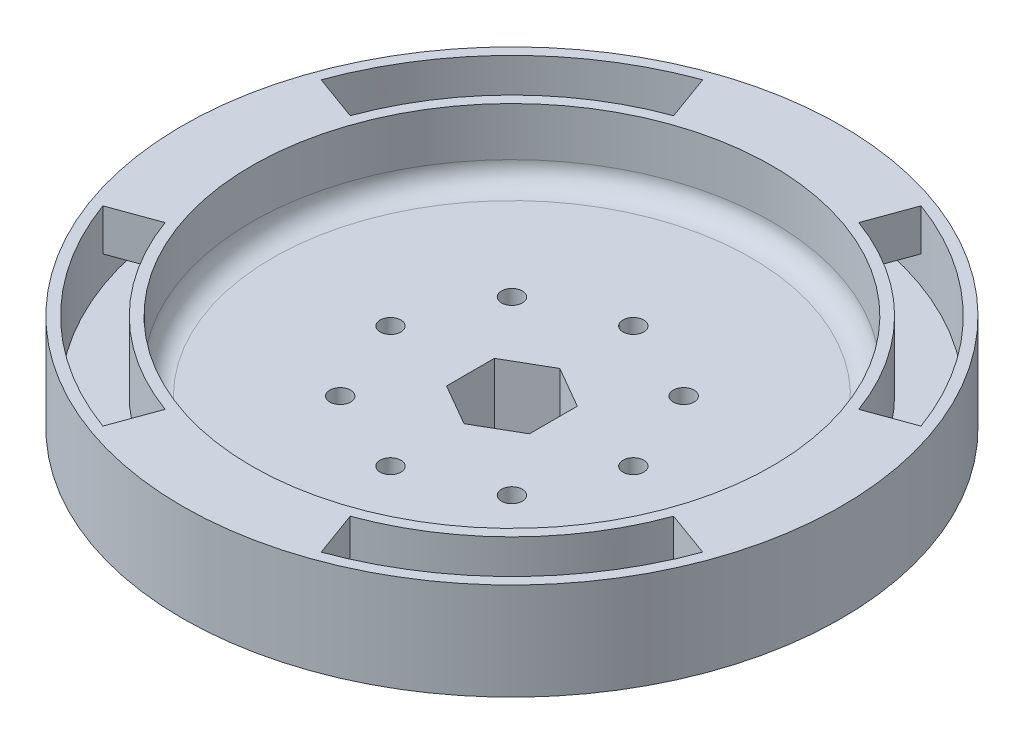
SolidWorks part; units mm, degrees
material "聚脂树脂"
ref_plane "前视基准面" through (0, 0, 0) normal (0, 0, 1) x (1, 0, 0)
ref_plane "上视基准面" through (0, 0, 0) normal (0, 1, 0) x (1, 0, 0)
ref_plane "右视基准面" through (0, 0, 0) normal (1, 0, 0) x (0, 0, -1)
other "Configuration Table"
sketch "草图1" plane through (0, 0, 0) normal (0, 1, 0) x (1, 0, 0)
  line L0 (0, 0) -> (29.5032, 0) construction
  line L1 (0, 0) -> (0, 22.1158) construction
  line L2 (0, 0) -> (19.7523, 19.7523) construction
  line L4 (0, 6.8993) -> (-5.975, 3.4497)
  line L5 (-5.975, 3.4497) -> (-5.975, -3.4497)
  line L6 (-5.975, -3.4497) -> (0, -6.8993)
  line L7 (0, -6.8993) -> (5.975, -3.4497)
  line L8 (5.975, -3.4497) -> (5.975, 3.4497)
  line L9 (5.975, 3.4497) -> (0, 6.8993)
  circle A0 centre (0, 0) radius 21.5
  circle A1 centre (12.3744, 12.3744) radius 1.5
  circle A3 centre (12.3744, -12.3744) radius 1.5
  circle A4 centre (-12.3744, -12.3744) radius 1.5
  circle A5 centre (-12.3744, 12.3744) radius 1.5
  circle A7 centre (0, 17.5) radius 1.5
  circle A8 centre (17.5, 0) radius 1.5
  circle A9 centre (0, -17.5) radius 1.5
  circle A10 centre (-17.5, 0) radius 1.5
  circle A11 centre (0, 0) radius 5.975 construction
  point P7 (0, 6.8993)
  point P25 (0, 0)
  dimension "D1" = 43
  dimension "D2" = 11.95
  dimension "D3" = 3
  dimension "D6" = 2
  dimension "D4" = 17.5
  dimension "D5" = 45
extrude "凸台-拉伸1" add sketch "草图1" along normal blind 4
sketch "草图9" plane through (0, 0, 0) normal (0, -1, 0) x (1, 0, 0)
  line L0 (-5.975, -3.4497) -> (-5.975, 3.4497) construction
  line L1 (0, -6.8993) -> (-5.975, -3.4497) construction
  line L2 (5.975, -3.4497) -> (0, -6.8993) construction
  line L3 (5.975, 3.4497) -> (5.975, -3.4497) construction
  line L4 (0, 6.8993) -> (5.975, 3.4497) construction
  line L5 (-5.975, 3.4497) -> (0, 6.8993) construction
  line L6 (-5.975, -3.4497) -> (-5.975, 3.4497)
  line L7 (0, -6.8993) -> (-5.975, -3.4497)
  line L8 (5.975, -3.4497) -> (0, -6.8993)
  line L9 (5.975, 3.4497) -> (5.975, -3.4497)
  line L10 (0, 6.8993) -> (5.975, 3.4497)
  line L11 (-5.975, 3.4497) -> (0, 6.8993)
  circle A0 centre (0, 0) radius 9.75
  dimension "D1" = 19.5
extrude "凸台-拉伸4" add sketch "草图9" along normal blind 5
sketch "草图10" plane through (0, -5, 0) normal (0, -1, 0) x (1, 0, 0)
  circle A0 centre (0, 0) radius 9.75
  circle A1 centre (0, 0) radius 2
  dimension "D1" = 4
  dimension "D2" = 19.5
extrude "凸台-拉伸5" add sketch "草图10" along normal blind 5
sketch "草图11" plane through (0, -10, 0) normal (0, -1, 0) x (1, 0, 0)
  line L0 (0, 0) -> (0, 28.5719) construction
  line L1 (0, 0) -> (35.6203, -20.5654) construction
  line L2 (0, 0) -> (-22.187, -12.8097) construction
  line L3 (2, 0) -> (8.8992, -3.9833)
  line L4 (1, -1.7321) -> (7.8992, -5.7153)
  line L5 (-1, -1.7321) -> (-7.8992, -5.7153)
  line L6 (-2, 0) -> (-8.8992, -3.9833)
  line L7 (1, 1.7321) -> (1, 9.6986)
  line L8 (-1, 1.7321) -> (-1, 9.6986)
  circle A0 centre (0, 0) radius 9.75 construction
  circle A1 centre (0, 0) radius 2 construction
  circle A2 centre (0, 0) radius 9.75 construction
  circle A3 centre (0, 0) radius 2 construction
  arc A4 (2, 0) -> (1, -1.7321) centre (0, 0) cw
  arc A5 (8.8992, -3.9833) -> (7.8992, -5.7153) centre (0, 0) cw
  arc A6 (-2, 0) -> (-1, -1.7321) centre (0, 0) ccw
  arc A7 (-8.8992, -3.9833) -> (-7.8992, -5.7153) centre (0, 0) ccw
  arc A8 (1, 9.6986) -> (-1, 9.6986) centre (0, 0) ccw
  arc A9 (1, 1.7321) -> (-1, 1.7321) centre (0, 0) ccw
  circle A10 centre (0, 0) radius 5
  circle M11 centre (0, 0) radius 9.75
  dimension "D4" = 10
  dimension "D1" = 120
  dimension "D2" = 120
  dimension "D3" = 2
extrude "凸台-拉伸6" add sketch "草图11" along normal blind 4 contours A10 L6 L5 M11 | A10 L7 L8 M11 | A10 L4 L3 M11
pattern_circular "阵列(圆周)1" count 2 every 60 about axis through (0, 0, 0) along (0, 1, 0) of "凸台-拉伸6"
sketch "草图12" plane through (0, 4, 0) normal (0, 1, 0) x (1, 0, 0)
  circle A0 centre (0, 0) radius 21.5
  circle A1 centre (0, 0) radius 47.5
  dimension "D1" = 43
  dimension "D2" = 95
extrude "凸台-拉伸7" add sketch "草图12" against normal blind 4
sketch "草图13" plane through (0, 4, 0) normal (0, 1, 0) x (1, 0, 0)
  circle A0 centre (0, 0) radius 37.5
  circle A1 centre (0, 0) radius 47.5
  circle A2 centre (0, 0) radius 39
  circle A3 centre (0, 0) radius 46
  circle M17 centre (0, 0) radius 47.5
  dimension "D1" = 95
  dimension "D2" = 75
  dimension "D3" = 78
  dimension "D4" = 92
extrude "凸台-拉伸8" add sketch "草图13" along normal blind 10 contours A2 A0 | A3 M17
sketch "草图14" plane through (0, 14, 0) normal (0, 1, 0) x (1, 0, 0)
  line L0 (-15.7329, 43.2259) -> (-13.3388, 36.648)
  line L1 (0, 43.5) -> (0, 39)
  line L2 (-13.3388, 36.648) -> (0, 0) construction
  line L3 (15.7329, 43.2259) -> (13.3388, 36.648)
  line L4 (43.2259, -15.7329) -> (36.648, -13.3388)
  line L5 (43.2259, 15.7329) -> (36.648, 13.3388)
  line L6 (-15.7329, -43.2259) -> (-13.3388, -36.648)
  line L7 (15.7329, -43.2259) -> (13.3388, -36.648)
  line L8 (-43.2259, 15.7329) -> (-36.648, 13.3388)
  line L9 (-43.2259, -15.7329) -> (-36.648, -13.3388)
  arc A0 (-13.3388, 36.648) -> (13.3388, 36.648) centre (0, 0) cw
  circle A1 centre (0, 0) radius 39 construction
  arc A2 (-15.7329, 43.2259) -> (15.7329, 43.2259) centre (0, 0) cw
  circle A3 centre (0, 0) radius 46 construction
  arc A4 (43.2259, 15.7329) -> (43.2259, -15.7329) centre (0, 0) cw
  arc A5 (36.648, 13.3388) -> (36.648, -13.3388) centre (0, 0) cw
  arc A6 (15.7329, -43.2259) -> (-15.7329, -43.2259) centre (0, 0) cw
  arc A7 (13.3388, -36.648) -> (-13.3388, -36.648) centre (0, 0) cw
  arc A8 (-43.2259, -15.7329) -> (-43.2259, 15.7329) centre (0, 0) cw
  arc A9 (-36.648, -13.3388) -> (-36.648, 13.3388) centre (0, 0) cw
  point P27 (0, 0)
  circle M8 centre (0, 0) radius 39
  dimension "D1" = 20
  dimension "D2" = 4
extrude "凸台-拉伸9" add sketch "草图14" against normal blind 6 contours A2 L0 L1 M8 | A2 L1 L3 M8 | A8 L9 L8 M8 | A6 L7 L6 M8 | A4 L5 L4 M8
fillet "圆角1" radius 3 1 edges at (0, 4, 37.5)
